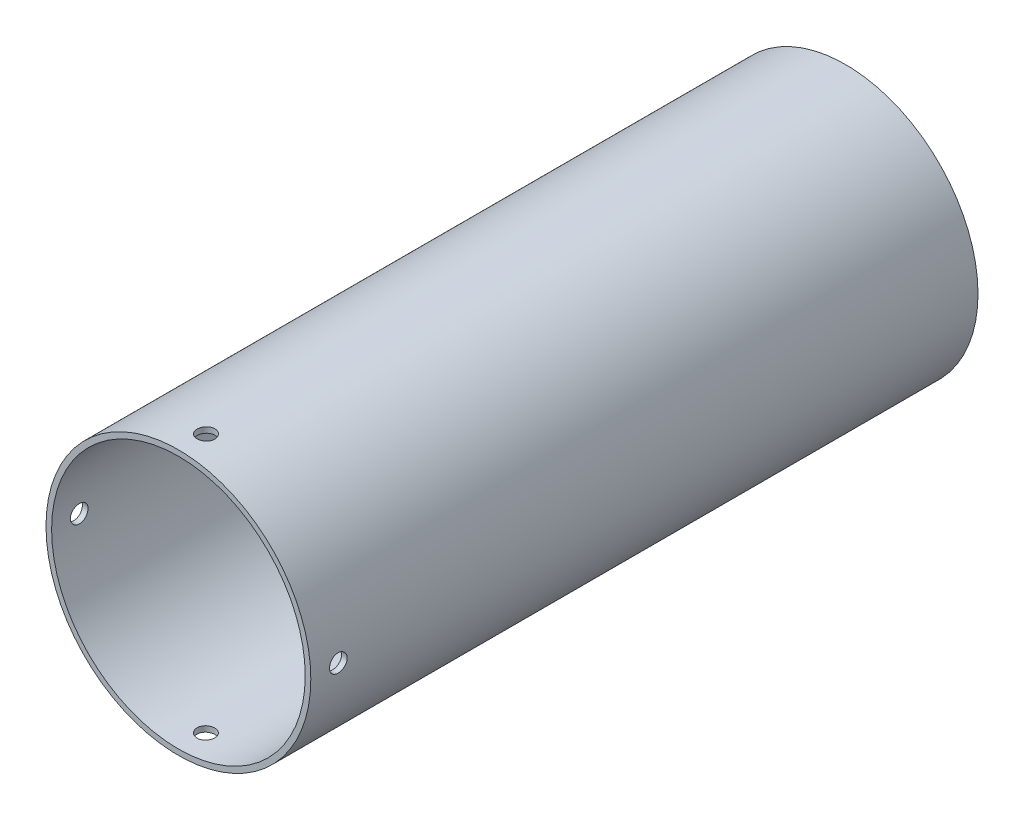
SolidWorks part; units mm, degrees
ref_plane "Front Plane" through (0, 0, 0) normal (0, 0, 1) x (1, 0, 0)
ref_plane "Top Plane" through (0, 0, 0) normal (0, 1, 0) x (1, 0, 0)
ref_plane "Right Plane" through (0, 0, 0) normal (1, 0, 0) x (0, 0, -1)
sketch "Sketch1" plane through (0, 0, 0) normal (0, 0, 1) x (1, 0, 0)
  circle A0 centre (0, 0) radius 23
  dimension "D1" = 46
extrude "Extrude-Thin1" add sketch "Sketch1" along normal blind 120 thin
sketch "Sketch2" plane through (0, 0, 0) normal (0, 0, -1) x (-1, 0, 0)
  circle A0 centre (0, 0) radius 24.016 construction
  circle A1 centre (0, 0) radius 24.016
extrude "Boss-Extrude1" add sketch "Sketch2" along normal blind 1.016
sketch "Sketch3" plane through (0, 0, 0) normal (0, 1, 0) x (1, 0, 0)
  line L0 (-24.016, -120) -> (24.016, -120) construction
  line L1 (-24.016, -120) -> (24.016, -120) construction
  circle A0 centre (0, -115) radius 1.6
  dimension "D1" = 3.2
  dimension "D2" = 5
extrude "Cut-Extrude1" cut sketch "Sketch3" against normal through all both and the other way through all
sketch "Sketch4" plane through (0, 0, 0) normal (1, 0, 0) x (0, 0, -1)
  line L0 (-120, 24.016) -> (-120, -24.016) construction
  line L1 (-120, 24.016) -> (-120, -24.016) construction
  circle A0 centre (-115, 0) radius 1.6
  dimension "D1" = 3.2
  dimension "D2" = 5
extrude "Cut-Extrude2" cut sketch "Sketch4" against normal through all both and the other way through all
equation "\"h\" = 120"
equation "\"d\" = 46"
equation "\"D1@Sketch1\"=\"d\""
equation "\"D1@Extrude-Thin1\"=\"h\""
